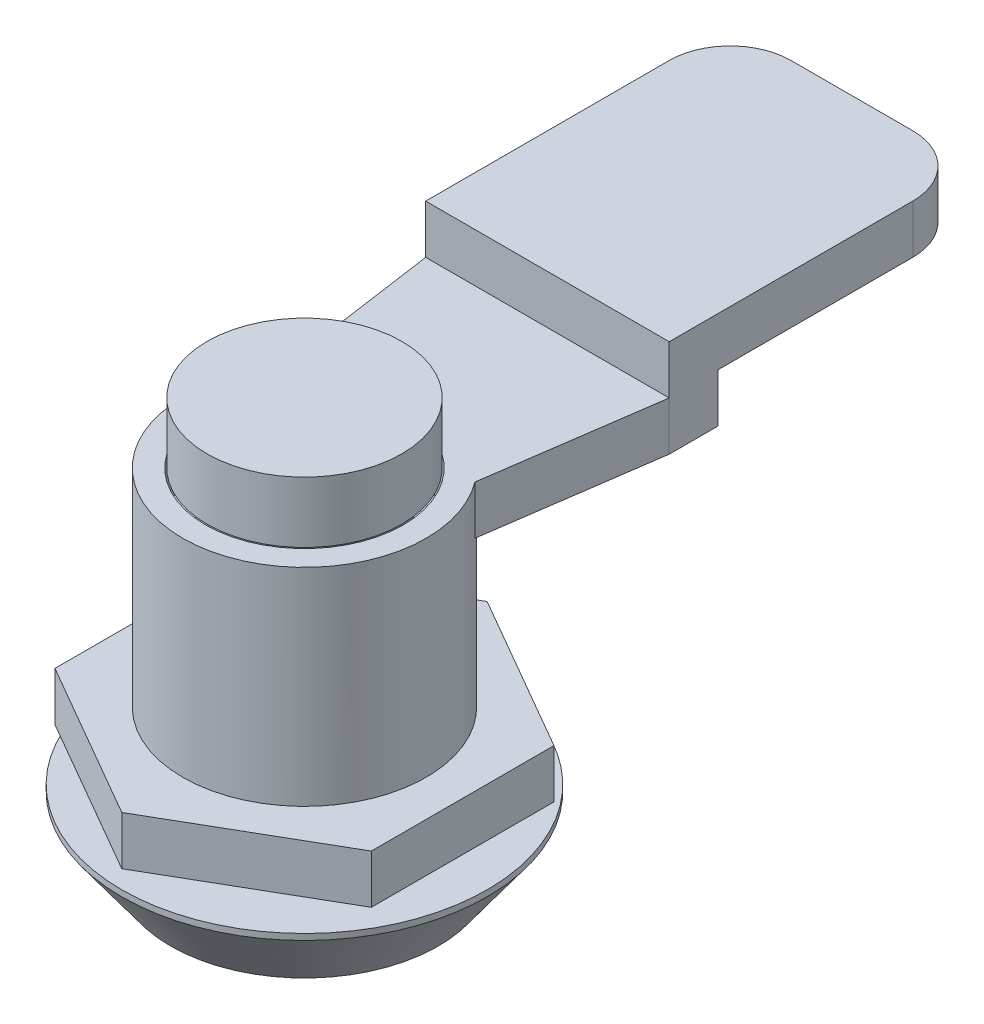
SolidWorks part; units mm, degrees
ref_plane "Спереди" through (0, 0, 0) normal (0, 0, 1) x (1, 0, 0)
ref_plane "Сверху" through (0, 0, 0) normal (0, 1, 0) x (1, 0, 0)
ref_plane "Справа" through (0, 0, 0) normal (1, 0, 0) x (0, 0, -1)
sketch "Эскиз1" plane through (0, 0, 0) normal (0, 0, 1) x (1, 0, 0)
  line L0 (0, 38.1343) -> (0, -36.2465) construction
  line L1 (0, 0) -> (11, 0)
  line L2 (11, 0) -> (15, 5.5)
  line L3 (15, 5.5) -> (15, 6)
  line L4 (15, 6) -> (10, 6)
  line L5 (10, 6) -> (10, 7.5)
  line L6 (10, 7.5) -> (15, 7.5)
  line L7 (15, 7.5) -> (15, 11.5)
  line L8 (15, 11.5) -> (10, 11.5)
  line L9 (10, 11.5) -> (10, 24.5)
  line L10 (10, 24.5) -> (6.3263, 24.5)
  line L11 (6.3263, 24.5) -> (6.3263, 28.5)
  line L12 (6.3263, 28.5) -> (8, 28.5)
  line L13 (8, 28.5) -> (8, 33.5)
  line L14 (8, 33.5) -> (0, 33.5)
  line L15 (0, 33.5) -> (0, 0)
  dimension "D1" = 11
  dimension "D2" = 15
  dimension "D3" = 10
  dimension "D4" = 10
  dimension "D5" = 8
  dimension "D6" = 4
  dimension "D8" = 6
  dimension "D9" = 0.5
  dimension "D10" = 1.5
  dimension "D11" = 4
  dimension "D12" = 5
  dimension "D13" = 18.5
revolve "Повернуть1" add sketch "Эскиз1" angle 360 about L0
sketch "Эскиз2" plane through (0, 24.5, 0) normal (0, 1, 0) x (1, 0, 0)
  line L0 (-8, 6) -> (-10, 19.954)
  line L1 (0, 24.0916) -> (0, -18.2995) construction
  line L2 (10, 19.954) -> (8, 6)
  line L3 (-10, 19.954) -> (-10, 23.954)
  line L4 (-10, 23.954) -> (10, 23.954)
  line L5 (10, 23.954) -> (10, 19.954)
  arc A0 (-8, 6) -> (8, 6) centre (0, 0) ccw
  circle A1 centre (0, 0) radius 8.1145
  circle A2 centre (0, 0) radius 10 construction
  dimension "D1" = 16
  dimension "D2" = 4
  dimension "D3" = 10
extrude "Вытянуть1" add sketch "Эскиз2" along normal up to surface (4 mm away) up to face at (0, 28.5, 8)
sketch "Эскиз4" plane through (0, 0, 0) normal (0, -1, 0) x (1, 0, 0)
  line L0 (-8.3943, 0) -> (8.2194, 0) construction
  circle A0 centre (0, 0) radius 9.25
  dimension "D1" = 18.5
extrude "Вырез-Вытянуть1" cut sketch "Эскиз4" against normal blind 5
sketch "Эскиз5" plane through (0, 11.5, 0) normal (0, 1, 0) x (1, 0, 0)
  line L1 (0, -15) -> (12.9904, -7.5)
  line L2 (12.9904, -7.5) -> (12.9904, 7.5)
  line L3 (12.9904, 7.5) -> (0, 15)
  line L4 (0, 15) -> (-12.9904, 7.5)
  line L5 (-12.9904, 7.5) -> (-12.9904, -7.5)
  line L6 (-12.9904, -7.5) -> (0, -15)
  circle A0 centre (0, 0) radius 12.9904 construction
  circle A1 centre (0, 0) radius 15 construction
extrude "Вырез-Вытянуть7" cut sketch "Эскиз5" against normal blind 4 flip side to cut
sketch "Эскиз6" plane through (0, 5, 0) normal (0, -1, 0) x (1, 0, 0)
  line L0 (-4.5, -3.8971) -> (0, 3.8971)
  line L1 (0, 3.8971) -> (4.5, -3.8971)
  line L2 (4.5, -3.8971) -> (-4.5, -3.8971)
  dimension "D1" = 9
  dimension "D2" = 9
  dimension "D3" = 9
  dimension "D4" = 7.7942
  dimension "D5" = 3.8971
  dimension "D6" = 4.5
extrude "Вытянуть3" add sketch "Эскиз6" along normal up to surface (5 mm away) up to face at (0, 0, -9.25)
sketch "Эскиз9" plane through (0, 0, -23.954) normal (0, 0, -1) x (-1, 0, 0)
  line L1 (-10, 28.5) -> (10, 28.5)
  line L2 (-10, 28.5) -> (-10, 32.5)
  line L3 (-10, 32.5) -> (10, 32.5)
  line L4 (10, 28.5) -> (10, 32.5)
  dimension "D1" = 20
  dimension "D2" = 4
extrude "Вытянуть4" add sketch "Эскиз9" along normal blind 21
sketch "Эскиз10" plane through (0, 33.5, 0) normal (0, 1, 0) x (1, 0, 0)
  line L0 (-21.469, 0) -> (18.7048, 0) construction
sketch "Эскиз11" plane through (0, 0, -23.954) normal (0, 0, 1) x (1, 0, 0)
  line L1 (10, 32.5) -> (-10, 32.5)
  line L2 (10, 32.5) -> (10, 28.5)
  line L3 (10, 28.5) -> (-10, 28.5)
  line L4 (-10, 32.5) -> (-10, 28.5)
extrude "Вытянуть5" add sketch "Эскиз11" along normal blind 4
fillet "Скругление1" radius 5 2 edges at (10, 30.5, -44.954) (-10, 30.5, -44.954)
equation "\"D5@Эскиз6\" = \"D4@Эскиз6\"/2"
equation "\"D6@Эскиз6\" = \"D1@Эскиз6\"/2"
